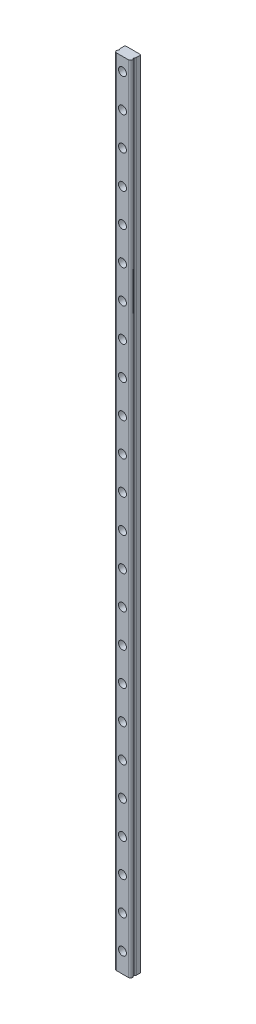
SolidWorks part; units mm, degrees
ref_plane "Front Plane" through (0, 0, 0) normal (0, 0, 1) x (1, 0, 0)
ref_plane "Top Plane" through (0, 0, 0) normal (0, 1, 0) x (1, 0, 0)
ref_plane "Right Plane" through (0, 0, 0) normal (1, 0, 0) x (0, 0, -1)
sketch "Sketch1" plane through (0, 0, 0) normal (0, 0, 1) x (1, 0, 0)
  line L1 (-6, 0) -> (6, 0)
  line L2 (-6, 0) -> (-6, 600)
  line L3 (-6, 600) -> (6, 600)
  line L4 (6, 0) -> (6, 600)
  dimension "D1" = 12
  dimension "D2" = 6
  dimension "D3" = 600
extrude "Boss-Extrude1" add sketch "Sketch1" along normal blind 8
sketch "Sketch2" plane through (0, 600, 0) normal (0, 1, 0) x (1, 0, 0)
  line L0 (-5.5, 0) -> (-6, -0.5)
  line L1 (6, 0) -> (-6, 0) construction
  line L2 (-6, -8) -> (-6, 0) construction
  line L3 (0, 0) -> (0, -8) construction
  line L4 (6, -8) -> (-6, -8) construction
  line L5 (-5.5, 0) -> (-7.7603, 0)
  line L6 (-7.7603, 0) -> (-7.7603, -8)
  line L7 (-7.7603, -8) -> (-4.5, -8)
  line L8 (-6, -0.5) -> (-6, -3.5)
  line L9 (6, -0.5) -> (6, -3.5)
  line L10 (7.7603, -8) -> (4.5, -8)
  line L11 (7.7603, 0) -> (7.7603, -8)
  line L12 (5.5, 0) -> (7.7603, 0)
  line L13 (5.5, 0) -> (6, -0.5)
  arc A0 (-5.4922, -5.375) -> (-4.5, -8) centre (-4.5, -6.5) ccw
  arc A1 (-6, -3.5) -> (-5.4922, -4.625) centre (-4.5, -3.5) ccw
  arc A2 (-5.4922, -4.625) -> (-5.4922, -5.375) centre (-5.8229, -5) cw
  arc A3 (5.4922, -4.625) -> (5.4922, -5.375) centre (5.8229, -5) ccw
  arc A4 (6, -3.5) -> (5.4922, -4.625) centre (4.5, -3.5) cw
  arc A5 (5.4922, -5.375) -> (4.5, -8) centre (4.5, -6.5) cw
  dimension "D3" = 3
  dimension "D4" = 3
  dimension "D5" = 0.5
  dimension "D1" = 0.5
  dimension "D2" = 0.5
extrude "Cut-Extrude1" cut sketch "Sketch2" against normal through all
sketch "Sketch3" plane through (0, 0, 8) normal (0, 0, 1) x (1, 0, 0)
  line L0 (4.5, 600) -> (-4.5, 600) construction
  circle A0 centre (0, 590) radius 3
  dimension "D1" = 6
  dimension "D2" = 10
extrude "Cut-Extrude2" cut sketch "Sketch3" against normal blind 4.5
sketch "Sketch4" plane through (0, 0, 3.5) normal (0, 0, 1) x (1, 0, 0)
  circle A0 centre (0, 590) radius 1.75
  dimension "D1" = 3.5
extrude "Cut-Extrude3" cut sketch "Sketch4" against normal through all
pattern_linear "LPattern1" count 24 spacing 25 along (0, -1, 0) of "Cut-Extrude2", "Cut-Extrude3"
